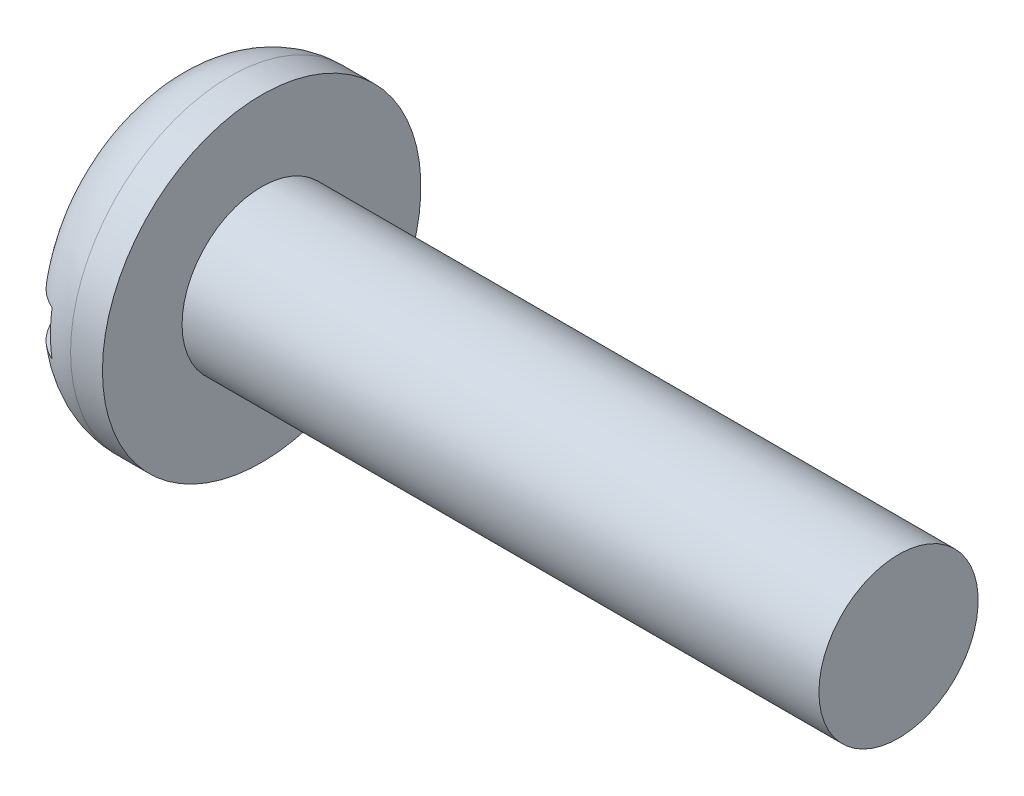
SolidWorks part; units mm, degrees
ref_plane "Plane1" through (0, 0, 0) normal (0, 0, 1) x (1, 0, 0)
ref_plane "Plane2" through (0, 0, 0) normal (0, 1, 0) x (1, 0, 0)
ref_plane "Plane3" through (0, 0, 0) normal (1, 0, 0) x (0, 0, -1)
sketch "BodySke" plane through (0, 0, 0) normal (0, 0, 1) x (1, 0, 0)
  line L0 (6, 5) -> (6, 10)
  line L1 (0, 0) -> (0, 6)
  line L2 (-25.4, 0) -> (127, 0) construction
  line L3 (46, 0) -> (0, 0)
  line L4 (6, 5) -> (46, 5)
  line L5 (46, 5) -> (46, 0)
  line L6 (4, 10) -> (6, 10)
  line L7 (6, -5) -> (46, -5) construction
  line L8 (0, -10) -> (6, -10) construction
  line L9 (7.5, 6.5875) -> (7.5, -2.9375) construction
  line L10 (6, 6.35) -> (6, -3.175) construction
  arc A0 (0, 6) -> (4, 10) centre (4, 6) cw
  point P15 (0, 10)
  dimension "Head_fillet_rad" = 4
  dimension "Diameter" = 10
  dimension "Length" = 40
  dimension "Head_ht" = 6
  dimension "Head_dia" = 20
  dimension "Advance" = 1.5
  dimension "Thread_nom" = 40
revolve "Base-Revolve" add sketch "BodySke" angle 360 about L2
cosmetic thread "ThreadCosmetic" [suppressed] parameters "Thread_length"=38.5, "Thread_minor"=8.344
sketch "Sketch2" plane through (0, 0, 0) normal (1, 0, 0) x (0, 0, -1)
  line L0 (10, -1.4) -> (-10, -1.4)
  line L1 (10, -1.4) -> (10, 1.4)
  line L2 (-10, 1.4) -> (10, 1.4)
  line L3 (-10, 1.4) -> (-10, -1.4)
  dimension "D1" = 20
  dimension "Slot_width" = 2.8
  dimension "D2" = 10
  dimension "D3" = 1.4
extrude "Slot" cut sketch "Sketch2" along normal blind 2.4
sketch "ThdSchSke" plane through (0, 0, 0) normal (0, 0, 1) x (1, 0, 0)
  line L0 (7.5, -4.172) -> (6.9202, -5)
  line L1 (7.5, -4.172) -> (8.0798, -5)
  line L2 (8.0798, -5) -> (8.0798, -6.25)
  line L3 (-3.175, 0) -> (5.1513, 0) construction
  line L5 (8.0798, -6.25) -> (6.9202, -6.25)
  line L6 (6.9202, -6.25) -> (6.9202, -5)
  dimension "Diameter" = 10
  dimension "SideAngle" = 55
  dimension "VeeAngle" = 70
  dimension "Thread_minor" = 8.344
  dimension "Overcut" = 12.5
  dimension "Start" = 7.5
revolve "ThreadSchematic" [suppressed] cut sketch "ThdSchSke" angle 360 about L3
pattern_linear "ThdSchPat" [suppressed]
equation "\"D1@Sketch2\" = \"Head_dia@BodySke\""
equation "\"D2@Sketch2\" = \"D1@Sketch2\" / 2"
equation "\"D3@Sketch2\" = \"Slot_width@Sketch2\" / 2"
equation "\"Thread_length@ThreadCosmetic\" = ((sgn( (\"Length@BodySke\" - \"Advance@BodySke\" ) - \"Thread_nom@BodySke\" )-1)*( (\"Length@BodySke\" - \"Advance@BodySke\" ) - \"Thread_nom@BodySke\" ))/-2+ \"Thread_nom@BodySke\""
equation "\"Thread_minor@ThdSchSke\" = \"Thread_minor@ThreadCosmetic\""
equation "\"Diameter@ThdSchSke\" = \"Diameter@BodySke\""
equation "\"Overcut@ThdSchSke\" = \"Diameter@BodySke\" * 1.25"
equation "\"Start@ThdSchSke\" = \"Head_ht@BodySke\" + \"Length@BodySke\" - \"Thread_length@ThreadCosmetic\"  '---Non-countersunk---"
equation "\"Num_threads@ThdSchPat\" = int( \"Thread_length@ThreadCosmetic\" / \"Advance@BodySke\" + 0.999 )  + 1"
equation "\"Advance@ThdSchPat\" = \"Thread_length@ThreadCosmetic\" /  (\"Num_threads@ThdSchPat\" - 1) 'relax it"
